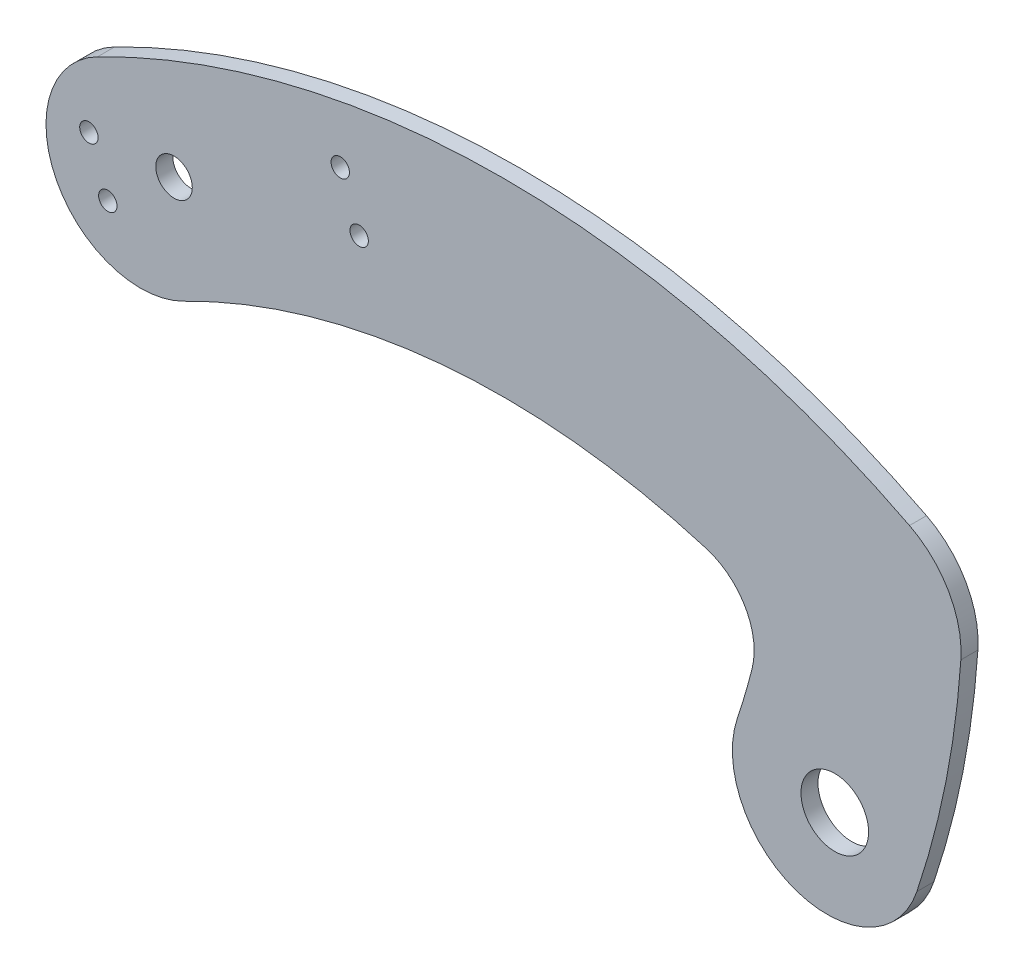
SolidWorks part; units mm, degrees
ref_plane "Front Plane" through (0, 0, 0) normal (0, 0, 1) x (1, 0, 0)
ref_plane "Top Plane" through (0, 0, 0) normal (0, 1, 0) x (1, 0, 0)
ref_plane "Right Plane" through (0, 0, 0) normal (1, 0, 0) x (0, 0, -1)
sketch "Sketch1" plane through (0, 0, 0) normal (0, 0, 1) x (1, 0, 0)
  line L84 (-8.0971, 15.8327) -> (8.0971, -15.8327) construction
  line L85 (144.3983, 15.8327) -> (128.2041, -15.8327) construction
  line L86 (0, 0) -> (136.3012, 0) construction
  arc A81 (-8.0971, 15.8327) -> (144.3983, 15.8327) centre (68.1506, -133.2589) cw
  arc A82 (8.0971, -15.8327) -> (128.2041, -15.8327) centre (68.1506, -133.2589) cw
  arc A84 (-8.0971, 15.8327) -> (8.0971, -15.8327) centre (0, 0) ccw
  arc A85 (144.3983, 15.8327) -> (128.2041, -15.8327) centre (136.3012, 0) cw
  point P0 (129.4388, -43.7338)
  dimension "D10" = 131.8914
  dimension "D11" = 35.5662
  dimension "D12" = 136.3012
extrude "Boss-Extrude1" add sketch "Sketch1" along normal blind 3.2004
sketch "Sketch2" plane through (0, 0, 3.2004) normal (0, 0, 1) x (1, 0, 0)
  line L0 (-8.0971, 15.8327) -> (8.0971, -15.8327) construction
  line L13 (6.2618, 3.4378) -> (6.6133, 2.5127) construction
  line L30 (6.6133, 2.5127) -> (0, 0) construction
  line L31 (37.4816, 20.6483) -> (41.0334, 11.3003) construction
  line L32 (-9.7258, 2.7121) -> (-6.1741, -6.6359) construction
  line L33 (39.2575, 15.9743) -> (-7.9499, -1.9619) construction
  circle A14 centre (41.0334, 11.3003) radius 1.7272
  circle A15 centre (-9.7258, 2.7121) radius 1.7272
  circle A16 centre (-6.1741, -6.6359) radius 1.7272
  circle A17 centre (37.4816, 20.6483) radius 1.7272
  circle A18 centre (6.2618, 3.4378) radius 3.429
  point P2 (39.921, 14.2353)
  point P4 (6.2618, 3.4378)
  dimension "D2" = 96.282
  dimension "D10" = 6.858
  dimension "D9" = 3.4544
  dimension "D11" = 50.5
  dimension "D12" = 15.203
  dimension "D13" = 10
  dimension "D14" = 7.0746
  dimension "D15" = 0.9896
extrude "Cut-Extrude1" cut sketch "Sketch2" against normal up to surface (3.2004 mm away) up to face at (68.1506, 4.1592, 0)
sketch "Sketch3" plane through (0, 0, 3.2004) normal (0, 0, 1) x (1, 0, 0)
  line L0 (136.3012, 0) -> (128.9162, -37.3774) construction
  line L1 (154.0439, -1.1985) -> (118.5586, 1.1985) construction
  line L5 (144.3983, 15.8327) -> (128.2041, -15.8327) construction
  line L6 (0, 0) -> (136.3012, 0) construction
  line L7 (112.0509, -31.7381) -> (145.7814, -43.0168) construction
  arc A0 (118.5586, 1.1985) -> (154.0439, -1.1985) centre (136.3012, 0) cw
  arc A2 (112.0509, -31.7381) -> (145.7814, -43.0168) centre (128.9162, -37.3774) ccw
  arc A3 (118.5586, 1.1985) -> (112.0509, -31.7381) centre (-13.033, 10.0872) cw
  arc A4 (154.0439, -1.1985) -> (145.7814, -43.0168) centre (-13.033, 10.0872) cw
  dimension "D1" = 131.8914
  dimension "D2" = 38.1
  dimension "D3" = 78.823
extrude "Boss-Extrude2" add sketch "Sketch3" against normal up to surface (3.2004 mm away) up to face at (39.3062, 11.3003, 0)
sketch "Sketch4" plane through (0, 0, 3.2004) normal (0, 0, 1) x (1, 0, 0)
  line L0 (112.0509, -31.7381) -> (145.7814, -43.0168) construction
  circle A0 centre (130.3615, -37.8607) radius 6.35
  point P2 (129.4729, -28.129)
  point P5 (126.9942, -50.5254)
  point P7 (0, 0)
  point P8 (0, 0)
  point P9 (0, 0)
  dimension "D10" = 12.7
  dimension "D2" = 1.524
extrude "Cut-Extrude2" cut sketch "Sketch4" against normal up to surface (3.2004 mm away) up to face at (93.6811, -9.2345, 0)
fillet "Fillet1" radius 12.7 1 edges at (117.1902, -10.8234, 1.6002)
